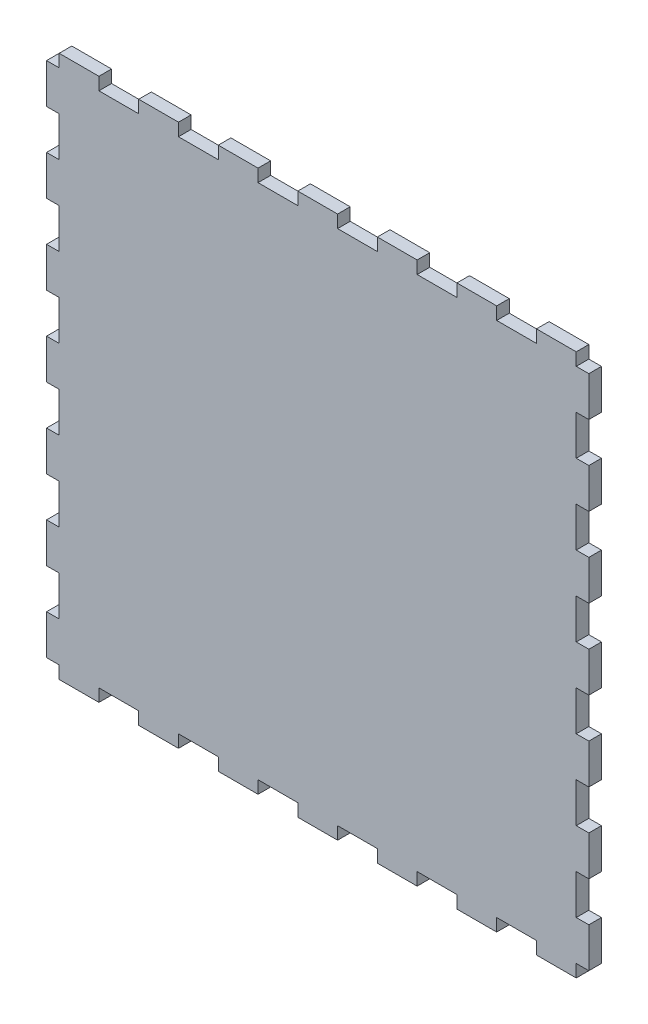
SolidWorks part; units mm, degrees
ref_plane "Front Plane" through (0, 0, 0) normal (0, 0, 1) x (1, 0, 0)
ref_plane "Top Plane" through (0, 0, 0) normal (0, 1, 0) x (1, 0, 0)
ref_plane "Right Plane" through (0, 0, 0) normal (1, 0, 0) x (0, 0, -1)
sketch "Sketch2" plane through (0, 0, 0) normal (0, 0, 1) x (1, 0, 0)
  line L0 (125, 250) -> (125, 0) construction
  line L1 (0, 0) -> (250, 0)
  line L2 (0, 0) -> (0, 250)
  line L3 (0, 250) -> (250, 250)
  line L4 (250, 0) -> (250, 250)
  line L5 (80.825, 169.175) -> (169.175, 169.175) construction
  line L6 (80.825, 169.175) -> (80.825, 80.825) construction
  line L7 (80.825, 80.825) -> (169.175, 80.825) construction
  line L8 (169.175, 169.175) -> (169.175, 80.825) construction
  line L9 (0, 125) -> (250, 125) construction
  line L10 (0, 250) -> (0, 256.096)
  line L19 (169.175, 80.825) -> (172.35, 80.825)
  line L20 (169.175, 80.825) -> (169.175, 104)
  line L21 (169.175, 104) -> (172.35, 104)
  line L22 (172.35, 80.825) -> (172.35, 104)
  line L23 (169.175, 80.825) -> (146, 80.825)
  line L25 (169.175, 77.65) -> (146, 77.65)
  line L26 (146, 80.825) -> (146, 77.65)
  line L31 (80.825, 80.825) -> (77.65, 80.825)
  line L32 (80.825, 80.825) -> (80.825, 104)
  line L33 (80.825, 104) -> (77.65, 104)
  line L34 (77.65, 80.825) -> (77.65, 104)
  line L35 (169.175, 169.175) -> (172.35, 169.175)
  line L36 (169.175, 169.175) -> (169.175, 146)
  line L37 (169.175, 146) -> (172.35, 146)
  line L38 (172.35, 169.175) -> (172.35, 146)
  line L39 (80.825, 169.175) -> (77.65, 169.175)
  line L40 (80.825, 169.175) -> (80.825, 146)
  line L41 (80.825, 146) -> (77.65, 146)
  line L42 (77.65, 169.175) -> (77.65, 146)
  line L43 (0, 256.096) -> (19.2308, 256.096)
  line L44 (19.2308, 256.096) -> (19.2308, 250)
  line L45 (38.4615, 256.096) -> (57.6923, 256.096)
  line L46 (57.6923, 256.096) -> (57.6923, 250)
  line L47 (38.4615, 250) -> (38.4615, 256.096)
  line L48 (76.9231, 256.096) -> (96.1538, 256.096)
  line L49 (96.1538, 256.096) -> (96.1538, 250)
  line L50 (76.9231, 250) -> (76.9231, 256.096)
  line L51 (115.3846, 256.096) -> (134.6154, 256.096)
  line L52 (134.6154, 256.096) -> (134.6154, 250)
  line L53 (115.3846, 250) -> (115.3846, 256.096)
  line L54 (153.8462, 256.096) -> (173.0769, 256.096)
  line L55 (173.0769, 256.096) -> (173.0769, 250)
  line L56 (153.8462, 250) -> (153.8462, 256.096)
  line L57 (192.3077, 256.096) -> (211.5385, 256.096)
  line L58 (211.5385, 256.096) -> (211.5385, 250)
  line L59 (192.3077, 250) -> (192.3077, 256.096)
  line L60 (230.7692, 256.096) -> (250, 256.096)
  line L61 (250, 256.096) -> (250, 250)
  line L62 (230.7692, 250) -> (230.7692, 256.096)
  line L63 (211.5385, 250) -> (230.7692, 250) construction
  line L64 (250, 250) -> (250, 0)
  line L65 (250, 250) -> (256.096, 250)
  line L66 (256.096, 250) -> (256.096, 230.7692)
  line L67 (256.096, 230.7692) -> (250, 230.7692)
  line L68 (256.096, 211.5385) -> (256.096, 192.3077)
  line L69 (256.096, 192.3077) -> (250, 192.3077)
  line L70 (250, 211.5385) -> (256.096, 211.5385)
  line L71 (256.096, 173.0769) -> (256.096, 153.8462)
  line L72 (256.096, 153.8462) -> (250, 153.8462)
  line L73 (250, 173.0769) -> (256.096, 173.0769)
  line L74 (256.096, 134.6154) -> (256.096, 115.3846)
  line L75 (256.096, 115.3846) -> (250, 115.3846)
  line L76 (250, 134.6154) -> (256.096, 134.6154)
  line L77 (256.096, 96.1538) -> (256.096, 76.9231)
  line L78 (256.096, 76.9231) -> (250, 76.9231)
  line L79 (250, 96.1538) -> (256.096, 96.1538)
  line L80 (256.096, 57.6923) -> (256.096, 38.4615)
  line L81 (256.096, 38.4615) -> (250, 38.4615)
  line L82 (250, 57.6923) -> (256.096, 57.6923)
  line L83 (256.096, 19.2308) -> (256.096, 0)
  line L84 (256.096, 0) -> (250, 0)
  line L85 (250, 19.2308) -> (256.096, 19.2308)
  line L86 (250, 38.4615) -> (250, 19.2308) construction
  line L87 (250, 0) -> (0, 0)
  line L88 (250, 0) -> (250, -6.096)
  line L89 (250, -6.096) -> (230.7692, -6.096)
  line L90 (230.7692, -6.096) -> (230.7692, 0)
  line L91 (211.5385, -6.096) -> (192.3077, -6.096)
  line L92 (192.3077, -6.096) -> (192.3077, 0)
  line L93 (211.5385, 0) -> (211.5385, -6.096)
  line L94 (173.0769, -6.096) -> (153.8462, -6.096)
  line L95 (153.8462, -6.096) -> (153.8462, 0)
  line L96 (173.0769, 0) -> (173.0769, -6.096)
  line L97 (134.6154, -6.096) -> (115.3846, -6.096)
  line L98 (115.3846, -6.096) -> (115.3846, 0)
  line L99 (134.6154, 0) -> (134.6154, -6.096)
  line L100 (96.1538, -6.096) -> (76.9231, -6.096)
  line L101 (76.9231, -6.096) -> (76.9231, 0)
  line L102 (96.1538, 0) -> (96.1538, -6.096)
  line L103 (57.6923, -6.096) -> (38.4615, -6.096)
  line L104 (38.4615, -6.096) -> (38.4615, 0)
  line L105 (57.6923, 0) -> (57.6923, -6.096)
  line L106 (19.2308, -6.096) -> (0, -6.096)
  line L107 (0, -6.096) -> (0, 0)
  line L108 (19.2308, 0) -> (19.2308, -6.096)
  line L109 (38.4615, 0) -> (19.2308, 0) construction
  line L110 (0, 0) -> (0, 250)
  line L111 (0, 0) -> (-6.096, 0)
  line L112 (-6.096, 0) -> (-6.096, 19.2308)
  line L113 (-6.096, 19.2308) -> (0, 19.2308)
  line L114 (-6.096, 38.4615) -> (-6.096, 57.6923)
  line L115 (-6.096, 57.6923) -> (0, 57.6923)
  line L116 (0, 38.4615) -> (-6.096, 38.4615)
  line L117 (-6.096, 76.9231) -> (-6.096, 96.1538)
  line L118 (-6.096, 96.1538) -> (0, 96.1538)
  line L119 (0, 76.9231) -> (-6.096, 76.9231)
  line L120 (-6.096, 115.3846) -> (-6.096, 134.6154)
  line L121 (-6.096, 134.6154) -> (0, 134.6154)
  line L122 (0, 115.3846) -> (-6.096, 115.3846)
  line L123 (-6.096, 153.8462) -> (-6.096, 173.0769)
  line L124 (-6.096, 173.0769) -> (0, 173.0769)
  line L125 (0, 153.8462) -> (-6.096, 153.8462)
  line L126 (-6.096, 192.3077) -> (-6.096, 211.5385)
  line L127 (-6.096, 211.5385) -> (0, 211.5385)
  line L128 (0, 192.3077) -> (-6.096, 192.3077)
  line L129 (-6.096, 230.7692) -> (-6.096, 250)
  line L130 (-6.096, 250) -> (0, 250)
  line L131 (0, 230.7692) -> (-6.096, 230.7692)
  line L132 (0, 211.5385) -> (0, 230.7692) construction
  line L133 (169.175, 77.65) -> (170.175, 77.65)
  line L134 (170.175, 77.65) -> (170.175, 80.825)
  line L135 (169.175, 80.825) -> (146, 80.825)
  line L136 (104, 80.825) -> (104, 77.65)
  line L137 (79.825, 77.65) -> (79.825, 80.825)
  line L138 (80.825, 77.65) -> (79.825, 77.65)
  line L139 (80.825, 77.65) -> (104, 77.65)
  line L140 (104, 80.825) -> (80.825, 80.825)
  line L141 (169.175, 172.35) -> (170.175, 172.35)
  line L142 (80.825, 172.35) -> (79.825, 172.35)
  line L143 (79.825, 172.35) -> (79.825, 169.175)
  line L144 (104, 169.175) -> (80.825, 169.175)
  line L145 (80.825, 172.35) -> (104, 172.35)
  line L146 (104, 169.175) -> (104, 172.35)
  line L147 (146, 169.175) -> (146, 172.35)
  line L148 (169.175, 172.35) -> (146, 172.35)
  line L149 (169.175, 169.175) -> (146, 169.175)
  line L150 (170.175, 172.35) -> (170.175, 169.175)
  line L152 (170.175, 77.65) -> (146, 77.65)
  line L153 (170.175, 77.65) -> (170.175, 80.825)
  line L154 (170.175, 80.825) -> (146, 80.825)
  line L155 (146, 77.65) -> (146, 80.825)
  line L156 (104, 77.65) -> (79.825, 77.65)
  line L157 (104, 77.65) -> (104, 80.825)
  line L158 (104, 80.825) -> (79.825, 80.825)
  line L159 (79.825, 77.65) -> (79.825, 80.825)
  line L160 (104, 169.175) -> (79.825, 169.175)
  line L161 (104, 169.175) -> (104, 172.35)
  line L162 (104, 172.35) -> (79.825, 172.35)
  line L163 (79.825, 169.175) -> (79.825, 172.35)
  line L164 (170.175, 169.175) -> (146, 169.175)
  line L165 (170.175, 169.175) -> (170.175, 172.35)
  line L166 (170.175, 172.35) -> (146, 172.35)
  line L167 (146, 169.175) -> (146, 172.35)
  point P13 (125, 169.175)
  point P14 (80.825, 125)
  point P43 (125, 125)
  dimension "D1" = 250
  dimension "D2" = 88.35
  dimension "D3" = 3.175
  dimension "D4" = 23.175
  dimension "D6" = 6.096
  dimension "D8" = 1
  dimension "D5" = 7
  dimension "D7" = 4
extrude "Boss-Extrude2" add sketch "Sketch2" along normal blind 6.096 contours L108 L1 L107 L106 | L105 L87 L104 L103 | L102 L87 L101 L100 | L99 L87 L98 L97 | L96 L87 L95 L94 | L93 L87 L92 L91 | L90 L89 L88 L87 | L85 L4 L84 L83 | L82 L64 L81 L80 | L79 L64 L78 L77 | L76 L64 L75 L74 | L73 L64 L72 L71 | L70 L64 L69 L68 | L67 L66 L65 L64 | L62 L3 L61 L60 | L59 L3 L58 L57 | L56 L3 L55 L54 | L53 L3 L52 L51 | L50 L3 L49 L48 | L47 L3 L46 L45 | L44 L43 L10 L3 | L131 L110 L130 L129 | L128 L2 L127 L126 | L125 L110 L124 L123 | L122 L2 L121 L120 | L119 L110 L118 L117 | L116 L2 L115 L114 | L113 L112 L111 L2
